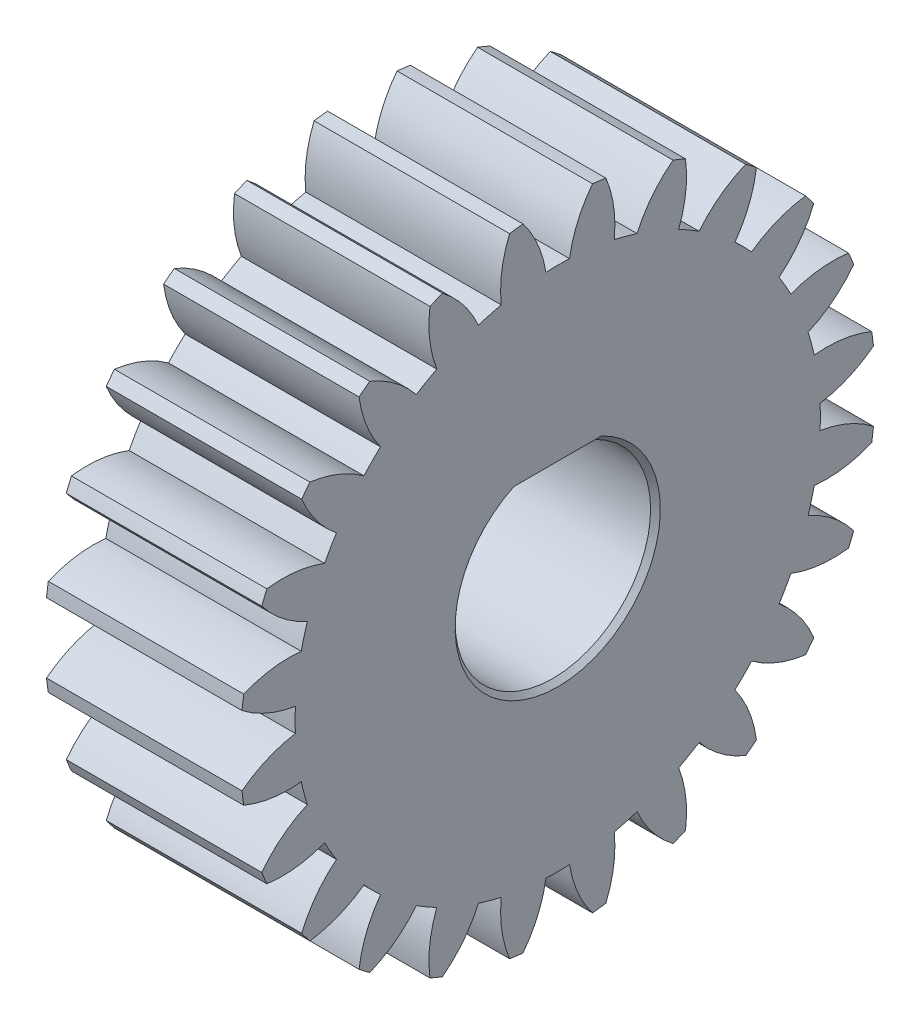
SolidWorks part; units mm, degrees
ref_plane "前视基准面" through (0, 0, 0) normal (0, 0, 1) x (1, 0, 0)
ref_plane "上视基准面" through (0, 0, 0) normal (0, 1, 0) x (1, 0, 0)
ref_plane "右视基准面" through (0, 0, 0) normal (1, 0, 0) x (0, 0, -1)
ref_plane "基准面4" through (0, 0, 0) normal (-1, 0, 0) x (0, -1, 0)
sketch "草图1" plane through (0, 0, 0) normal (-1, 0, 0) x (0, -1, 0)
  line L0 (-1.8, -0.8718) -> (-1.8, 0.8718)
  arc A0 (-0.7113, 6.461) -> (-0.9851, 6.4249) centre (0, 0) ccw
  arc A1 (-0.9851, 6.4249) -> (-1.1561, 5.2482) centre (1.2304, 5.5023) ccw
  arc A2 (-1.1561, 5.2482) -> (-1.6229, 5.1231) centre (0, 0) ccw
  arc A3 (-1.6229, 5.1231) -> (-2.3593, 6.0567) centre (-3.8167, 4.1499) ccw
  arc A4 (-2.3593, 6.0567) -> (-2.6144, 5.951) centre (0, 0) ccw
  arc A5 (-2.6144, 5.951) -> (-2.475, 4.7701) centre (-0.2356, 5.6332) ccw
  arc A6 (-2.475, 4.7701) -> (-2.8936, 4.5285) centre (0, 0) ccw
  arc A7 (-2.8936, 4.5285) -> (-3.8465, 5.2397) centre (-4.7607, 3.0206) ccw
  arc A8 (-3.8465, 5.2397) -> (-4.0656, 5.0716) centre (0, 0) ccw
  arc A9 (-4.0656, 5.0716) -> (-3.6253, 3.967) centre (-1.6855, 5.3803) ccw
  arc A10 (-3.6253, 3.967) -> (-3.967, 3.6253) centre (0, 0) ccw
  arc A11 (-3.967, 3.6253) -> (-5.0716, 4.0656) centre (-5.3803, 1.6855) ccw
  arc A12 (-5.0716, 4.0656) -> (-5.2397, 3.8465) centre (0, 0) ccw
  arc A13 (-5.2397, 3.8465) -> (-4.5285, 2.8936) centre (-3.0206, 4.7607) ccw
  arc A14 (-4.5285, 2.8936) -> (-4.7701, 2.475) centre (0, 0) ccw
  arc A15 (-4.7701, 2.475) -> (-5.951, 2.6144) centre (-5.6332, 0.2356) ccw
  arc A16 (-5.951, 2.6144) -> (-6.0567, 2.3593) centre (0, 0) ccw
  arc A17 (-6.0567, 2.3593) -> (-5.1231, 1.6229) centre (-4.1499, 3.8167) ccw
  arc A18 (-5.1231, 1.6229) -> (-5.2482, 1.1561) centre (0, 0) ccw
  arc A19 (-5.2482, 1.1561) -> (-6.4249, 0.9851) centre (-5.5023, -1.2304) ccw
  arc A20 (-6.4249, 0.9851) -> (-6.461, 0.7113) centre (0, 0) ccw
  arc A21 (-6.461, 0.7113) -> (-5.3686, 0.2416) centre (-4.9963, 2.6126) ccw
  arc A22 (-5.3686, 0.2416) -> (-5.3686, -0.2416) centre (0, 0) ccw
  arc A23 (-5.3686, -0.2416) -> (-6.461, -0.7113) centre (-4.9963, -2.6126) ccw
  arc A24 (-6.461, -0.7113) -> (-6.4249, -0.9851) centre (0, 0) ccw
  arc A25 (-6.4249, -0.9851) -> (-5.2482, -1.1561) centre (-5.5023, 1.2304) ccw
  arc A26 (-5.2482, -1.1561) -> (-5.1231, -1.6229) centre (0, 0) ccw
  arc A27 (-5.1231, -1.6229) -> (-6.0567, -2.3593) centre (-4.1499, -3.8167) ccw
  arc A28 (-6.0567, -2.3593) -> (-5.951, -2.6144) centre (0, 0) ccw
  arc A29 (-5.951, -2.6144) -> (-4.7701, -2.475) centre (-5.6332, -0.2356) ccw
  arc A30 (-4.7701, -2.475) -> (-4.5285, -2.8936) centre (0, 0) ccw
  arc A31 (-4.5285, -2.8936) -> (-5.2397, -3.8465) centre (-3.0206, -4.7607) ccw
  arc A32 (-5.2397, -3.8465) -> (-5.0716, -4.0656) centre (0, 0) ccw
  arc A33 (-5.0716, -4.0656) -> (-3.967, -3.6253) centre (-5.3803, -1.6855) ccw
  arc A34 (-3.967, -3.6253) -> (-3.6253, -3.967) centre (0, 0) ccw
  arc A35 (-3.6253, -3.967) -> (-4.0656, -5.0716) centre (-1.6855, -5.3803) ccw
  arc A36 (-4.0656, -5.0716) -> (-3.8465, -5.2397) centre (0, 0) ccw
  arc A37 (-3.8465, -5.2397) -> (-2.8936, -4.5285) centre (-4.7607, -3.0206) ccw
  arc A38 (-2.8936, -4.5285) -> (-2.475, -4.7701) centre (0, 0) ccw
  arc A39 (-2.475, -4.7701) -> (-2.6144, -5.951) centre (-0.2356, -5.6332) ccw
  arc A40 (-2.6144, -5.951) -> (-2.3593, -6.0567) centre (0, 0) ccw
  arc A41 (-2.3593, -6.0567) -> (-1.6229, -5.1231) centre (-3.8167, -4.1499) ccw
  arc A42 (-1.6229, -5.1231) -> (-1.1561, -5.2482) centre (0, 0) ccw
  arc A43 (-1.1561, -5.2482) -> (-0.9851, -6.4249) centre (1.2304, -5.5023) ccw
  arc A44 (-0.9851, -6.4249) -> (-0.7113, -6.461) centre (0, 0) ccw
  arc A45 (-0.7113, -6.461) -> (-0.2416, -5.3686) centre (-2.6126, -4.9963) ccw
  arc A46 (-0.2416, -5.3686) -> (0.2416, -5.3686) centre (0, 0) ccw
  arc A47 (0.2416, -5.3686) -> (0.7113, -6.461) centre (2.6126, -4.9963) ccw
  arc A48 (0.7113, -6.461) -> (0.9851, -6.4249) centre (0, 0) ccw
  arc A49 (0.9851, -6.4249) -> (1.1561, -5.2482) centre (-1.2304, -5.5023) ccw
  arc A50 (1.1561, -5.2482) -> (1.6229, -5.1231) centre (0, 0) ccw
  arc A51 (1.6229, -5.1231) -> (2.3593, -6.0567) centre (3.8167, -4.1499) ccw
  arc A52 (2.3593, -6.0567) -> (2.6144, -5.951) centre (0, 0) ccw
  arc A53 (2.6144, -5.951) -> (2.475, -4.7701) centre (0.2356, -5.6332) ccw
  arc A54 (2.475, -4.7701) -> (2.8936, -4.5285) centre (0, 0) ccw
  arc A55 (2.8936, -4.5285) -> (3.8465, -5.2397) centre (4.7607, -3.0206) ccw
  arc A56 (3.8465, -5.2397) -> (4.0656, -5.0716) centre (0, 0) ccw
  arc A57 (4.0656, -5.0716) -> (3.6253, -3.967) centre (1.6855, -5.3803) ccw
  arc A58 (3.6253, -3.967) -> (3.967, -3.6253) centre (0, 0) ccw
  arc A59 (3.967, -3.6253) -> (5.0716, -4.0656) centre (5.3803, -1.6855) ccw
  arc A60 (5.0716, -4.0656) -> (5.2397, -3.8465) centre (0, 0) ccw
  arc A61 (5.2397, -3.8465) -> (4.5285, -2.8936) centre (3.0206, -4.7607) ccw
  arc A62 (4.5285, -2.8936) -> (4.7701, -2.475) centre (0, 0) ccw
  arc A63 (4.7701, -2.475) -> (5.951, -2.6144) centre (5.6332, -0.2356) ccw
  arc A64 (5.951, -2.6144) -> (6.0567, -2.3593) centre (0, 0) ccw
  arc A65 (6.0567, -2.3593) -> (5.1231, -1.6229) centre (4.1499, -3.8167) ccw
  arc A66 (5.1231, -1.6229) -> (5.2482, -1.1561) centre (0, 0) ccw
  arc A67 (5.2482, -1.1561) -> (6.4249, -0.9851) centre (5.5023, 1.2304) ccw
  arc A68 (6.4249, -0.9851) -> (6.461, -0.7113) centre (0, 0) ccw
  arc A69 (6.461, -0.7113) -> (5.3686, -0.2416) centre (4.9963, -2.6126) ccw
  arc A70 (5.3686, -0.2416) -> (5.3686, 0.2416) centre (0, 0) ccw
  arc A71 (5.3686, 0.2416) -> (6.461, 0.7113) centre (4.9963, 2.6126) ccw
  arc A72 (6.461, 0.7113) -> (6.4249, 0.9851) centre (0, 0) ccw
  arc A73 (6.4249, 0.9851) -> (5.2482, 1.1561) centre (5.5023, -1.2304) ccw
  arc A74 (5.2482, 1.1561) -> (5.1231, 1.6229) centre (0, 0) ccw
  arc A75 (5.1231, 1.6229) -> (6.0567, 2.3593) centre (4.1499, 3.8167) ccw
  arc A76 (6.0567, 2.3593) -> (5.951, 2.6144) centre (0, 0) ccw
  arc A77 (5.951, 2.6144) -> (4.7701, 2.475) centre (5.6332, 0.2356) ccw
  arc A78 (4.7701, 2.475) -> (4.5285, 2.8936) centre (0, 0) ccw
  arc A79 (4.5285, 2.8936) -> (5.2397, 3.8465) centre (3.0206, 4.7607) ccw
  arc A80 (5.2397, 3.8465) -> (5.0716, 4.0656) centre (0, 0) ccw
  arc A81 (5.0716, 4.0656) -> (3.967, 3.6253) centre (5.3803, 1.6855) ccw
  arc A82 (3.967, 3.6253) -> (3.6253, 3.967) centre (0, 0) ccw
  arc A83 (3.6253, 3.967) -> (4.0656, 5.0716) centre (1.6855, 5.3803) ccw
  arc A84 (4.0656, 5.0716) -> (3.8465, 5.2397) centre (0, 0) ccw
  arc A85 (3.8465, 5.2397) -> (2.8936, 4.5285) centre (4.7607, 3.0206) ccw
  arc A86 (2.8936, 4.5285) -> (2.475, 4.7701) centre (0, 0) ccw
  arc A87 (2.475, 4.7701) -> (2.6144, 5.951) centre (0.2356, 5.6332) ccw
  arc A88 (2.6144, 5.951) -> (2.3593, 6.0567) centre (0, 0) ccw
  arc A89 (2.3593, 6.0567) -> (1.6229, 5.1231) centre (3.8167, 4.1499) ccw
  arc A90 (1.6229, 5.1231) -> (1.1561, 5.2482) centre (0, 0) ccw
  arc A91 (1.1561, 5.2482) -> (0.9851, 6.4249) centre (-1.2304, 5.5023) ccw
  arc A92 (0.9851, 6.4249) -> (0.7113, 6.461) centre (0, 0) ccw
  arc A93 (0.7113, 6.461) -> (0.2416, 5.3686) centre (2.6126, 4.9963) ccw
  arc A94 (0.2416, 5.3686) -> (-0.2416, 5.3686) centre (0, 0) ccw
  arc A95 (-0.2416, 5.3686) -> (-0.7113, 6.461) centre (-2.6126, 4.9963) ccw
  arc A96 (-1.8, 0.8718) -> (-1.8, -0.8718) centre (0, 0) cw
extrude "凸台-拉伸1" add sketch "草图1" against normal blind 4
chamfer "倒角1" distance 0.1 angle 45 4 edges at (0, 1.8, 0) (0, -2, 0) (4, 1.8, 0) (4, -2, 0)
